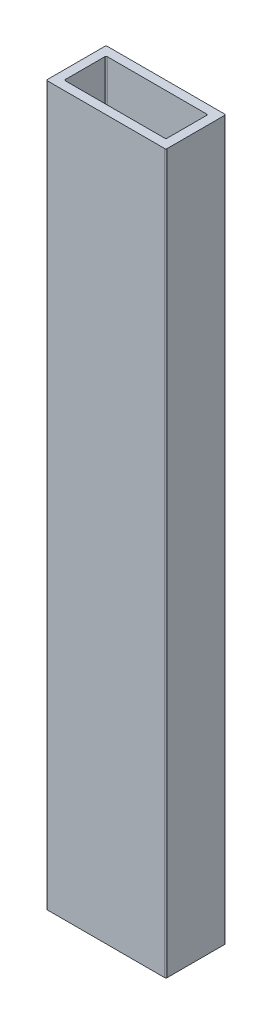
SolidWorks part; units mm, degrees
ref_plane "Спереди" through (0, 0, 0) normal (0, 0, 1) x (1, 0, 0)
ref_plane "Сверху" through (0, 0, 0) normal (0, 1, 0) x (1, 0, 0)
ref_plane "Справа" through (0, 0, 0) normal (1, 0, 0) x (0, 0, -1)
sketch "Эскиз1" plane through (0, 0, 0) normal (0, 1, 0) x (1, 0, 0)
  line L0 (8.5, 3.5) -> (-8.5, 3.5)
  line L1 (10, 5) -> (-10, 5)
  line L2 (10, 5) -> (10, -5)
  line L3 (10, -5) -> (-10, -5)
  line L4 (-10, 5) -> (-10, -5)
  line L5 (10, 5) -> (-10, -5) construction
  line L6 (10, -5) -> (-10, 5) construction
  line L7 (-8.5, 3.5) -> (-8.5, -3.5)
  line L8 (8.5, -3.5) -> (-8.5, -3.5)
  line L9 (8.5, 3.5) -> (8.5, -3.5)
  point P0 (0, 0)
  dimension "D1" = 20
  dimension "D2" = 10
  dimension "D3" = 1.5
extrude "Бобышка-Вытянуть1" add sketch "Эскиз1" along normal blind 120
fillet "Скругление1" radius 0.2 8 edges at (-10, 60, 5) (10, 60, -5) (8.5, 60, -3.5) (8.5, 60, 3.5) (-8.5, 60, 3.5) (-8.5, 60, -3.5) (-10, 60, -5) (10, 60, 5)
